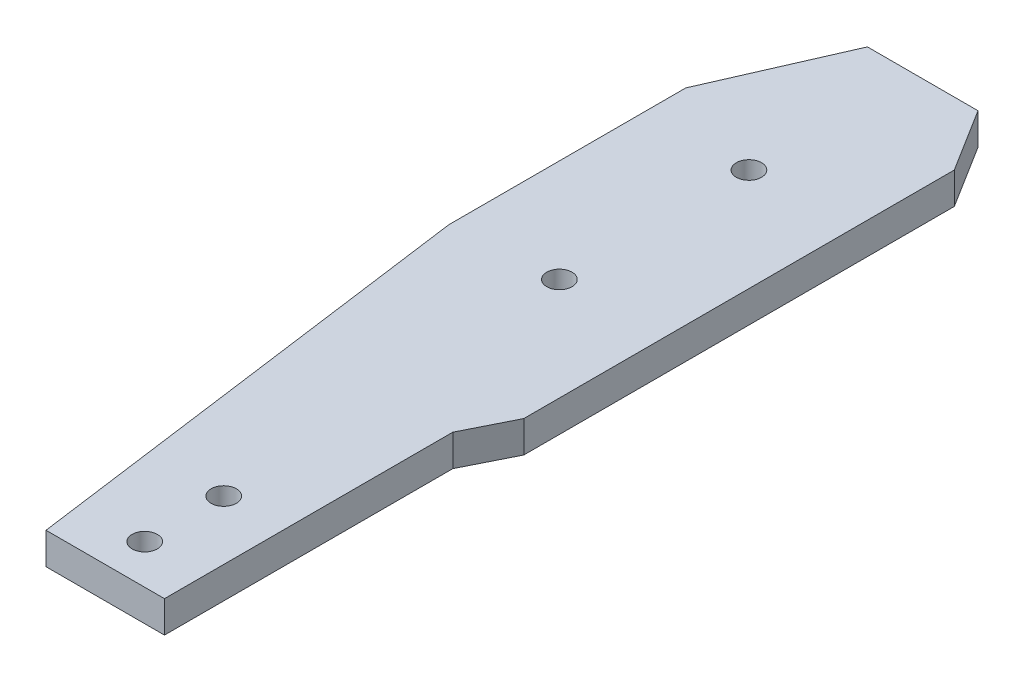
SolidWorks part; units mm, degrees
ref_plane "Front Plane" through (0, 0, 0) normal (0, 0, 1) x (1, 0, 0)
ref_plane "Top Plane" through (0, 0, 0) normal (0, 1, 0) x (1, 0, 0)
ref_plane "Right Plane" through (0, 0, 0) normal (1, 0, 0) x (0, 0, -1)
sketch "Sketch1" plane through (0, 0, 0) normal (0, 1, 0) x (1, 0, 0)
  line L0 (-7, -16) -> (-7, -46)
  line L1 (-7, -46) -> (1, -105)
  line L2 (1, -105) -> (16, -105)
  line L3 (16, -105) -> (16, -68.5)
  line L5 (16, -68.5) -> (19, -62.5)
  line L6 (19, -62.5) -> (19, -8)
  line L7 (19, -8) -> (14, 0)
  line L8 (14, 0) -> (0, 0)
  line L9 (0, 0) -> (-7, -16)
  dimension "D1" = 30
  dimension "D2" = 16
  dimension "D3" = 14
  dimension "D4" = 8
  dimension "D5" = 5
  dimension "D6" = 105
  dimension "D7" = 6
  dimension "D8" = 15
  dimension "D9" = 36.5
  dimension "D10" = 3
  dimension "D11" = 26
extrude "Boss-Extrude1" add sketch "Sketch1" along normal blind 4
sketch "Sketch2" plane through (0, 4, 0) normal (0, 1, 0) x (1, 0, 0)
  line L0 (19, -62.5) -> (19, -8) construction
  line L1 (14, 0) -> (0, 0) construction
  line L2 (16, -105) -> (16, -68.5) construction
  line L3 (1, -105) -> (16, -105) construction
  circle A0 centre (6, -21) radius 1.6
  circle A1 centre (6, -45) radius 1.6
  circle A2 centre (8.5, -90) radius 1.6
  circle A3 centre (8.5, -100) radius 1.6
  dimension "D1" = 3.2
  dimension "D3" = 21
  dimension "D4" = 3.2
  dimension "D5" = 3.2
  dimension "D6" = 3.2
  dimension "D7" = 24
  dimension "D8" = 7.5
  dimension "D9" = 10
  dimension "D10" = 5
  dimension "D2" = 13
extrude "Cut-Extrude1" cut sketch "Sketch2" against normal blind 4
